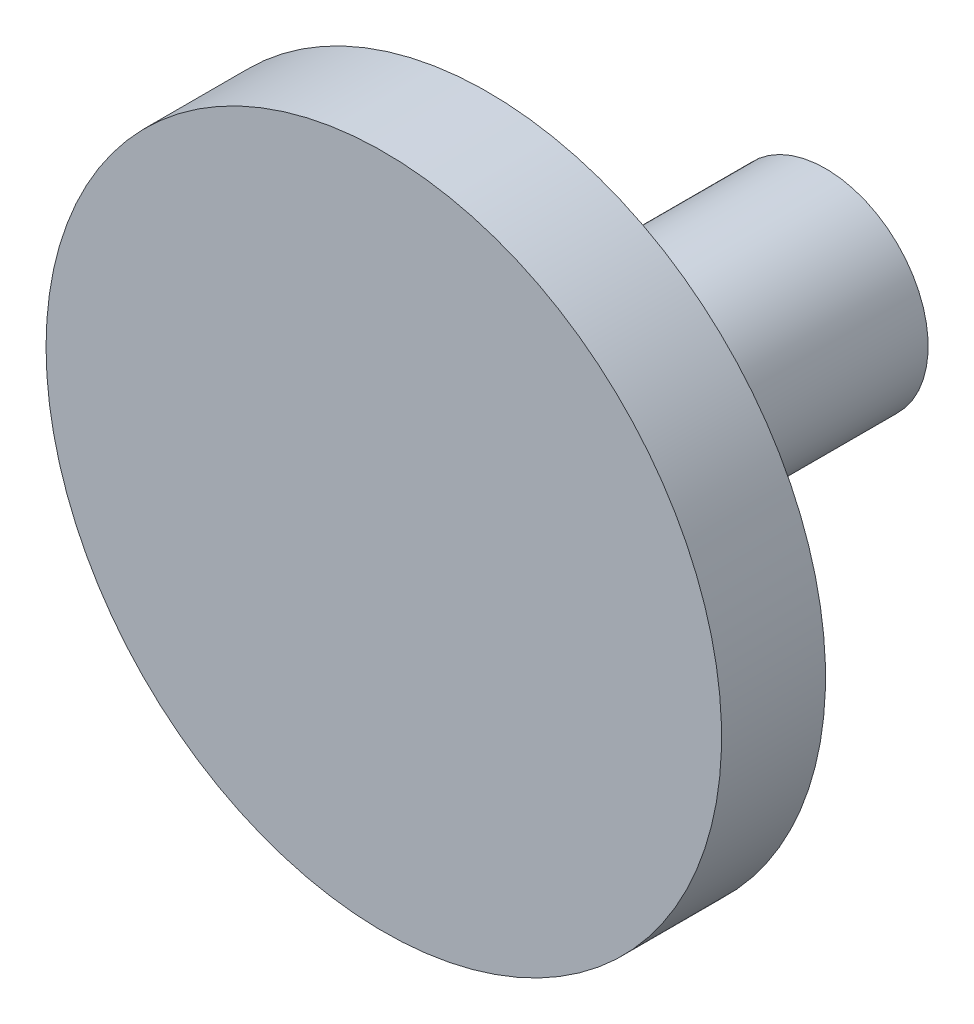
SolidWorks part; units mm, degrees
ref_plane "Alzado" through (0, 0, 0) normal (0, 0, 1) x (1, 0, 0)
ref_plane "Planta" through (0, 0, 0) normal (0, 1, 0) x (1, 0, 0)
ref_plane "Vista lateral" through (0, 0, 0) normal (1, 0, 0) x (0, 0, -1)
sketch "Croquis2" plane through (0, 0, 0) normal (0, 1, 0) x (1, 0, 0)
  line L0 (15.994, 0) -> (-15.994, 0) construction
  line L1 (0, 21.8204) -> (0, -10.2641) construction
  line L2 (-13, 0) -> (-13, 4)
  line L3 (-13, 4) -> (-5.5, 4)
  line L4 (-5.5, 4) -> (-5.5, 7)
  line L5 (-5.5, 7) -> (-3.95, 7)
  line L6 (-3.95, 7) -> (-3.95, 17)
  line L7 (-3.95, 17) -> (0, 17)
  line L8 (-13, 0) -> (0, 0)
  line L9 (0, 17) -> (0, 0)
  point P7 (0, 0)
  point P14 (0, 0)
  point P15 (0, 21.8204)
  dimension "D1" = 13
  dimension "D2" = 4
  dimension "D3" = 3
  dimension "D4" = 10
  dimension "D5" = 3.95
  dimension "D6" = 1.55
revolve "Revolución1" add sketch "Croquis2" angle 360 about L1
